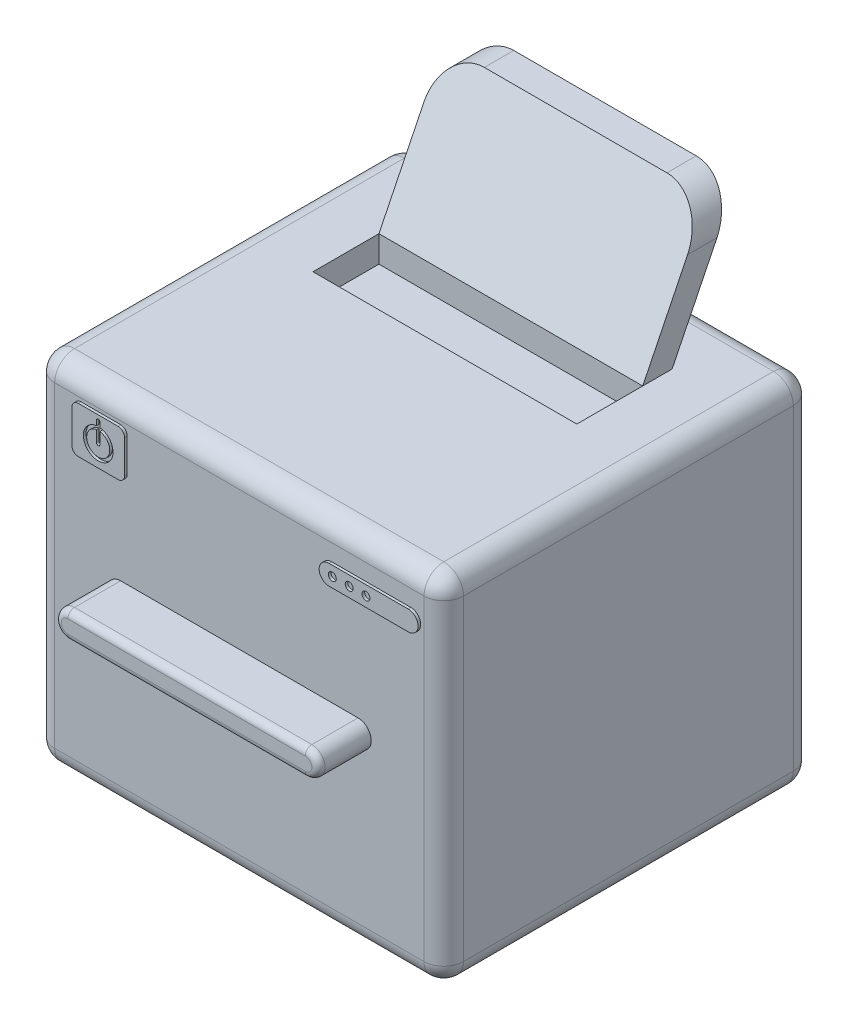
SolidWorks part; units mm, degrees
material "ABS"
ref_plane "Front" through (0, 0, 0) normal (0, 0, 1) x (1, 0, 0)
ref_plane "Top" through (0, 0, 0) normal (0, 1, 0) x (1, 0, 0)
ref_plane "Right" through (0, 0, 0) normal (1, 0, 0) x (0, 0, -1)
sketch "Sketch1" plane through (0, 0, 0) normal (0, 0, 1) x (1, 0, 0)
  line L0 (133.4483, 300.2587) -> (667.2416, 300.2587) construction
  line L2 (-196.85, 342.9) -> (196.85, 342.9)
  line L3 (-196.85, 342.9) -> (-196.85, 0)
  line L4 (-196.85, 0) -> (196.85, 0)
  line L5 (196.85, 342.9) -> (196.85, 0)
  point P6 (598.6296, 59.0815)
  point P7 (597.7642, 60.1586)
  dimension "D1" = 342.9
  dimension "D2" = 393.7
extrude "Boss-Extrude1" add sketch "Sketch1" along normal blind 355.6
sketch "Sketch2" plane through (0, 0, 355.6) normal (0, 0, 1) x (1, 0, 0)
  line L0 (196.85, 342.9) -> (-196.85, 342.9) construction
  line L1 (-158.75, 320.675) -> (-107.95, 320.675)
  line L2 (-158.75, 320.675) -> (-158.75, 276.225)
  line L3 (-158.75, 276.225) -> (-107.95, 276.225)
  line L4 (-107.95, 320.675) -> (-107.95, 276.225)
  line L5 (-158.75, 320.675) -> (-107.95, 276.225) construction
  line L6 (-158.75, 276.225) -> (-107.95, 320.675) construction
  line L7 (-196.85, 342.9) -> (-196.85, 0) construction
  point P0 (-133.35, 298.45)
  dimension "D1" = 44.45
  dimension "D2" = 63.5
  dimension "D3" = 44.45
  dimension "D4" = 50.8
extrude "Boss-Extrude2" add sketch "Sketch2" along normal blind 2.54
sketch "Sketch3" plane through (0, 0, 355.6) normal (0, 0, 1) x (1, 0, 0)
  line L0 (88.9, 298.45) -> (165.1, 298.45) construction
  line L1 (88.9, 307.975) -> (165.1, 307.975)
  line L2 (88.9, 288.925) -> (165.1, 288.925)
  line L5 (-107.95, 298.45) -> (88.9, 298.45) construction
  line L7 (-107.95, 276.225) -> (-107.95, 320.675) construction
  line L8 (196.85, 0) -> (196.85, 342.9) construction
  arc A0 (88.9, 307.975) -> (88.9, 288.925) centre (88.9, 298.45) ccw
  arc A1 (165.1, 288.925) -> (165.1, 307.975) centre (165.1, 298.45) ccw
  point P2 (127, 298.45)
  point P7 (473.4662, 364.9586)
  point P8 (473.4662, 364.9586)
  point P9 (473.4662, 358.6086)
  point P15 (489.3888, 364.9586)
  point P17 (527.9142, 379.7862)
  dimension "D1" = 19.05
  dimension "D2" = 76.2
  dimension "D3" = 31.75
extrude "Boss-Extrude3" add sketch "Sketch3" along normal blind 2.54
sketch "Sketch4" plane through (0, 0, 358.14) normal (0, 0, 1) x (1, 0, 0)
  line L0 (79.375, 298.45) -> (174.625, 298.45) construction
  arc A0 (88.9, 307.975) -> (88.9, 288.925) centre (88.9, 298.45) ccw construction
  arc A1 (165.1, 288.925) -> (165.1, 307.975) centre (165.1, 298.45) ccw construction
  circle A2 centre (92.075, 298.45) radius 3.81
  circle A3 centre (108.2865, 298.45) radius 3.81
  circle A4 centre (124.4979, 298.45) radius 3.81
  point P14 (0, 0)
  dimension "D1" = 7.62
  dimension "D2" = 16.2115
  dimension "D3" = 16.2115
  dimension "D4" = 12.7
extrude "Cut-Extrude1" cut sketch "Sketch4" against normal blind 2.54
sketch "Sketch5" plane through (0, 0, 355.6) normal (0, 0, 1) x (1, 0, 0)
  line L0 (-114.3, 177.8) -> (114.3, 177.8) construction
  line L1 (-114.3, 190.5) -> (114.3, 190.5)
  line L2 (-114.3, 165.1) -> (114.3, 165.1)
  line L3 (0, 177.8) -> (0, 342.9) construction
  line L4 (196.85, 342.9) -> (-196.85, 342.9) construction
  arc A0 (-114.3, 190.5) -> (-114.3, 165.1) centre (-114.3, 177.8) ccw
  arc A1 (114.3, 165.1) -> (114.3, 190.5) centre (114.3, 177.8) ccw
  point P2 (0, 177.8)
  dimension "D1" = 228.6
  dimension "D2" = 25.4
  dimension "D3" = 165.1
extrude "Boss-Extrude4" add sketch "Sketch5" along normal blind 50.8
fillet "Fillet1" radius 6.35 4 edges at (127, 177.8, 406.4) (0, 165.1, 406.4) (-127, 177.8, 406.4) (0, 190.5, 406.4)
fillet "Fillet2" radius 6.35 4 edges at (-158.75, 276.225, 356.87) (-107.95, 276.225, 356.87) (-107.95, 320.675, 356.87) (-158.75, 320.675, 356.87)
sketch "Sketch6" plane through (0, 0, 358.14) normal (0, 0, 1) x (1, 0, 0)
  line L0 (-133.35, 296.545) -> (-133.35, 276.225) construction
  line L3 (-133.35, 296.545) -> (-133.35, 315.595) construction
  line L4 (-134.9375, 296.545) -> (-134.9375, 315.595)
  line L5 (-131.7625, 296.545) -> (-131.7625, 315.595)
  line L6 (-152.4, 276.225) -> (-114.3, 276.225) construction
  circle A1 centre (-133.35, 296.545) radius 11.1125
  circle A2 centre (-133.35, 296.545) radius 14.2875
  arc A3 (-134.9375, 296.545) -> (-131.7625, 296.545) centre (-133.35, 296.545) ccw
  arc A4 (-131.7625, 315.595) -> (-134.9375, 315.595) centre (-133.35, 315.595) ccw
  point P0 (268.36, 377.642)
  point P12 (-133.35, 306.07)
  dimension "D2" = 22.225
  dimension "D3" = 3.175
  dimension "D4" = 19.05
  dimension "D5" = 20.32
  dimension "D1" = 3.175
extrude "Cut-Extrude2" cut sketch "Sketch6" against normal blind 2.54 contours L4 A2 L5 A1 | L5 A4 L4 A2 | L5 A2 L4 A1 | L4 A3 L5 A1
fillet "Fillet3" radius 19.05 12 edges at (-196.85, 171.45, 0) (-196.85, 171.45, 355.6) (196.85, 171.45, 0) (196.85, 171.45, 355.6) (0, 0, 0) (0, 0, 355.6) (0, 342.9, 0) (0, 342.9, 355.6) (-196.85, 342.9, 177.8) (196.85, 0, 177.8) (-196.85, 0, 177.8) (196.85, 342.9, 177.8)
sketch "Sketch7" plane through (0, 0, 0) normal (1, 0, 0) x (0, 0, -1)
  line L0 (-65.8773, 342.9) -> (-3.487, 469.9)
  line L1 (-336.55, 342.9) -> (-19.05, 342.9) construction
  line L2 (-94.1768, 342.9) -> (-31.7865, 469.9)
  line L3 (-31.7865, 469.9) -> (-3.487, 469.9)
  line L4 (-94.1768, 342.9) -> (-65.8773, 342.9)
  dimension "D1" = 25.4
  dimension "D2" = 127
extrude "Boss-Extrude5" add sketch "Sketch7" along normal mid plane 254
fillet "Fillet4" radius 39.116 2 edges at (-127, 469.9, 17.6368) (127, 469.9, 17.6368)
sketch "Sketch8" plane through (0, 342.9, 0) normal (0, 1, 0) x (1, 0, 0)
  line L0 (0, -94.1768) -> (0, -125.9268) construction
  line L1 (127, -94.1768) -> (-127, -94.1768) construction
  line L3 (-127, -157.6768) -> (127, -157.6768)
  line L4 (-127, -157.6768) -> (-127, -94.1768)
  line L5 (-127, -94.1768) -> (127, -94.1768)
  line L6 (127, -157.6768) -> (127, -94.1768)
  line L7 (-127, -157.6768) -> (127, -94.1768) construction
  line L8 (-127, -94.1768) -> (127, -157.6768) construction
  dimension "D1" = 63.5
  dimension "D2" = 254
extrude "Cut-Extrude3" cut sketch "Sketch8" against normal blind 25.4
equation "\"D3@Sketch4\"=\"D2@Sketch4\""
